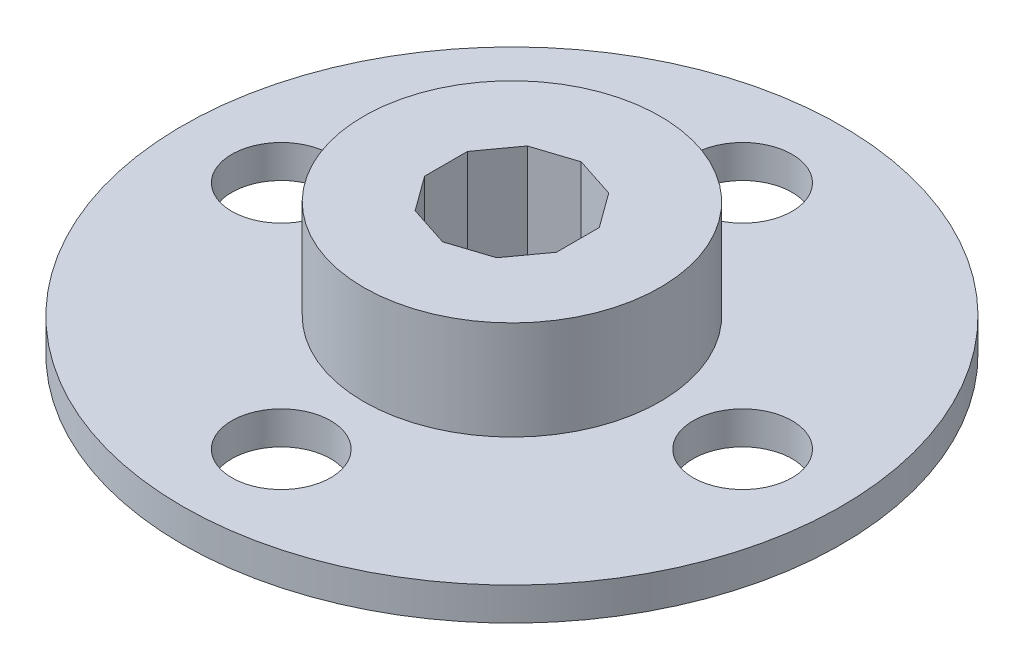
SolidWorks part; units mm, degrees
ref_plane "Front Plane" through (0, 0, 0) normal (0, 0, 1) x (1, 0, 0)
ref_plane "Top Plane" through (0, 0, 0) normal (0, 1, 0) x (1, 0, 0)
ref_plane "Right Plane" through (0, 0, 0) normal (1, 0, 0) x (0, 0, -1)
sketch "Sketch1" plane through (0, 0, 0) normal (0, 1, 0) x (1, 0, 0)
  circle A4 centre (0, 0) radius 7 construction
  circle A5 centre (0, 7) radius 1.5
  circle A6 centre (7, 0) radius 1.5
  circle A7 centre (0, -7) radius 1.5
  circle A8 centre (-7, 0) radius 1.5
  circle A9 centre (0, 0) radius 10
  circle A10 centre (0, 0) radius 4.5
  point P14 (0, 0)
  dimension "D1" = 9
  dimension "D2" = 3
  dimension "D4" = 20
  dimension "D5" = 14
  dimension "D3" = 4
extrude "Boss-Extrude1" add sketch "Sketch1" along normal blind 1
sketch "Sketch2" plane through (0, 1, 0) normal (0, 1, 0) x (1, 0, 0)
  line L1 (2, 0.6498) -> (1.2361, 1.7013)
  line L2 (1.2361, 1.7013) -> (0, 2.1029)
  line L3 (0, 2.1029) -> (-1.2361, 1.7013)
  line L4 (-1.2361, 1.7013) -> (-2, 0.6498)
  line L5 (-2, 0.6498) -> (-2, -0.6498)
  line L6 (-2, -0.6498) -> (-1.2361, -1.7013)
  line L7 (-1.2361, -1.7013) -> (0, -2.1029)
  line L8 (0, -2.1029) -> (1.2361, -1.7013)
  line L9 (1.2361, -1.7013) -> (2, -0.6498)
  line L10 (2, -0.6498) -> (2, 0.6498)
  circle A0 centre (0, 0) radius 2 construction
  circle A1 centre (0, 0) radius 4.5
  dimension "D2" = 9
  dimension "D1" = 4
extrude "Boss-Extrude2" add sketch "Sketch2" along normal blind 3
